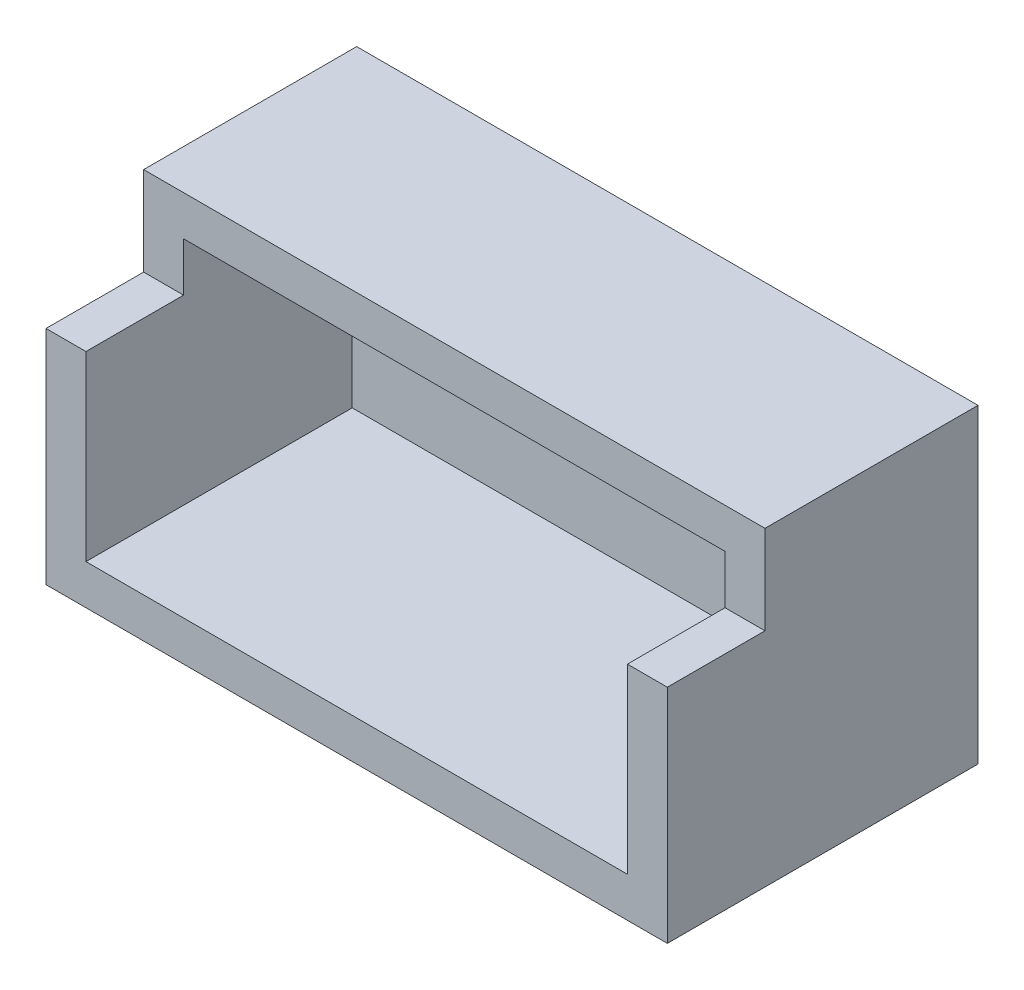
SolidWorks part; units mm, degrees
ref_plane "Front Plane" through (0, 0, 0) normal (0, 0, 1) x (1, 0, 0)
ref_plane "Top Plane" through (0, 0, 0) normal (0, 1, 0) x (1, 0, 0)
ref_plane "Right Plane" through (0, 0, 0) normal (1, 0, 0) x (0, 0, -1)
sketch "Soft_contact_and_wrap_profile" plane through (0, 0, 0) normal (0, 0, 1) x (1, 0, 0)
  line L1 (14, -21) -> (28, -21)
  line L2 (14, -21) -> (14, -14)
  line L3 (14, -14) -> (28, -14)
  line L4 (28, -21) -> (28, -14)
  dimension "D1" = 14
  dimension "D2" = 7
extrude "Soft_contact_and_wrap" add sketch "Soft_contact_and_wrap_profile" along normal blind 7 from offset 1
sketch "Finger_slip_pocket_profile" plane through (0, 0, 0) normal (0, 0, 1) x (1, 0, 0)
  line L1 (14.9, -20.1) -> (27.1, -20.1)
  line L2 (14.9, -20.1) -> (14.9, -14.9)
  line L3 (14.9, -14.9) -> (27.1, -14.9)
  line L4 (27.1, -20.1) -> (27.1, -14.9)
  dimension "D1" = 12.2
  dimension "D2" = 5.2
extrude "Open_top_slip_pocket" cut sketch "Finger_slip_pocket_profile" along normal blind 7
sketch "Servo_ear_sweep_relief_profile" plane through (0, 0, 0) normal (0, 0, 1) x (1, 0, 0)
  line L1 (13, -16) -> (29, -16)
  line L2 (13, -16) -> (13, -13)
  line L3 (13, -13) -> (29, -13)
  line L4 (29, -16) -> (29, -13)
  dimension "D1" = 16
  dimension "D2" = 3
extrude "Servo_ear_sweep_relief" cut sketch "Servo_ear_sweep_relief_profile" along normal blind 3.2 from offset 3.8
sketch "Pad_capture_M2_profile" plane through (0, 0, 0) normal (0, 0, 1) x (1, 0, 0)
  circle A0 centre (18, -17.5) radius 1.1
  circle A1 centre (24, -17.5) radius 1.1
  dimension "D1" = 2.2
  dimension "D2" = 2.2
extrude "Pad_capture_M2" cut sketch "Pad_capture_M2_profile" along normal through all from offset 50
